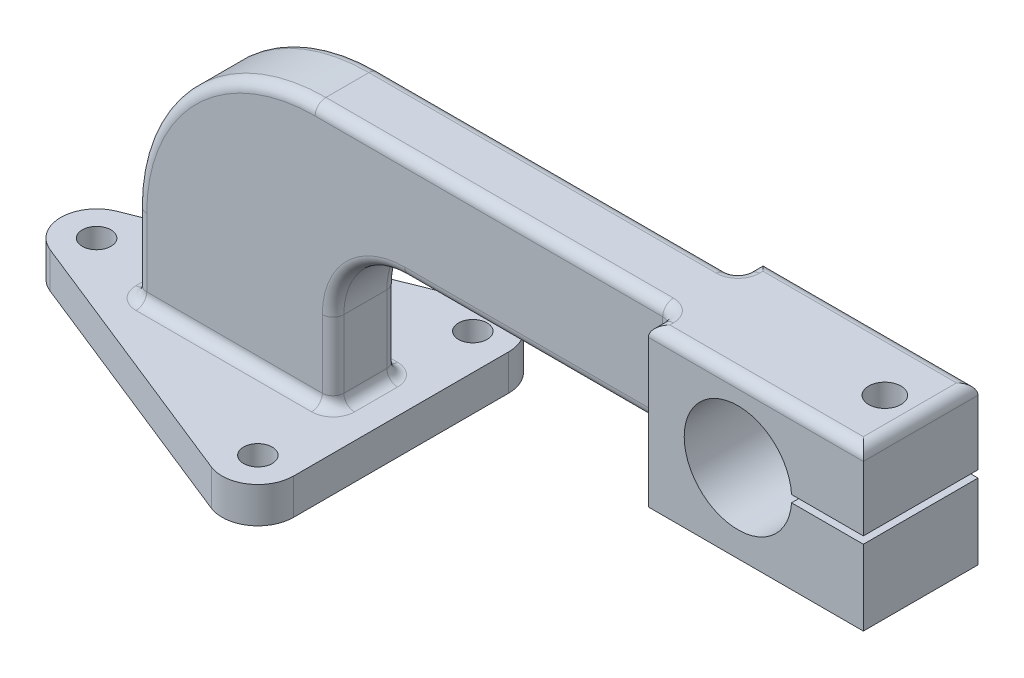
SolidWorks part; units mm, degrees
material "Zoltek Panex 33"
ref_plane "Front Plane" through (0, 0, 0) normal (0, 0, 1) x (1, 0, 0)
ref_plane "Top Plane" through (0, 0, 0) normal (0, 1, 0) x (1, 0, 0)
ref_plane "Right Plane" through (0, 0, 0) normal (1, 0, 0) x (0, 0, -1)
sketch "Sketch1" plane through (0, 0, 0) normal (0, 0, 1) x (1, 0, 0)
  line L0 (-112.5, 7.6863) -> (-57.5, 7.6863)
  line L1 (-57.5, 7.6863) -> (-57.5, 29.6863)
  line L2 (-37.5, 49.6863) -> (37.5, 49.6863)
  line L3 (37.5, 49.6863) -> (37.5, 79.6863)
  line L4 (37.5, 79.6863) -> (-62.5, 79.6863)
  line L5 (-112.5, 29.6863) -> (-112.5, 7.6863)
  arc A0 (-57.5, 29.6863) -> (-37.5, 49.6863) centre (-37.5, 29.6863) cw
  arc A1 (-62.5, 79.6863) -> (-112.5, 29.6863) centre (-62.5, 29.6863) ccw
  point P10 (0, 49.6863)
  point P11 (-132.8554, 79.6863)
  point P13 (0, 0)
  point P14 (0, 0)
  point P15 (0, 0)
  point P16 (-112.5, 29.6863)
  dimension "D3" = 20
  dimension "D4" = 50
  dimension "D1" = 55
  dimension "D2" = 30
  dimension "D5" = 95
  dimension "D6" = 22
  dimension "D7" = 22
extrude "Boss-Extrude1" add sketch "Sketch1" along normal mid plane 18
sketch "Sketch3" plane through (0, 7.6863, 0) normal (0, -1, 0) x (1, 0, 0)
  line L0 (-112.5, 0) -> (-57.5, 0) construction
  line L1 (-112.5, 9) -> (-112.5, -9) construction
  line L2 (-57.5, 9) -> (-57.5, -9) construction
  line L3 (-47.5, 30) -> (-47.5, -30)
  line L4 (-61.2139, -39.2848) -> (-136.2139, -9.2848)
  line L5 (-136.2139, 9.2848) -> (-61.2139, 39.2848)
  line L6 (-159.4258, 0) -> (-47.5, 0) construction
  arc A0 (-47.5, 30) -> (-61.2139, 39.2848) centre (-57.5, 30) ccw
  arc A1 (-47.5, -30) -> (-61.2139, -39.2848) centre (-57.5, -30) cw
  arc A2 (-136.2139, -9.2848) -> (-136.2139, 9.2848) centre (-132.5, 0) cw
  circle A3 centre (-132.5, 0) radius 4
  circle A4 centre (-57.5, -30) radius 4
  circle A5 centre (-57.5, 30) radius 4
  point P21 (0, 0)
  point P22 (0, 0)
  line M9 (-112.5, -9) -> (-57.5, -9)
  line M10 (-57.5, -9) -> (-57.5, 9)
  line M11 (-57.5, 9) -> (-112.5, 9)
  line M12 (-112.5, 9) -> (-112.5, -9)
  dimension "D1" = 10
  dimension "D5" = 8
  dimension "D2" = 30
  dimension "D3" = 75
  dimension "D4" = 20
extrude "Boss-Extrude2" add sketch "Sketch3" along normal blind 10 contours A2 L4 A1 L3 A0 L5 A5 A4 A3 M9 M12 M11 M10 | M12 M9 M10 M11
sketch "Sketch4" plane through (37.5, 0, 0) normal (1, 0, 0) x (0, 0, -1)
  line L0 (0, 79.6863) -> (0, 49.6863) construction
  line L1 (-9, 79.6863) -> (9, 79.6863) construction
  line L2 (-9, 49.6863) -> (9, 49.6863) construction
  line L3 (-16, 79.6863) -> (16, 79.6863)
  line L4 (16, 79.6863) -> (16, 35.6863)
  line L5 (16, 35.6863) -> (-16, 35.6863)
  line L6 (-16, 35.6863) -> (-16, 79.6863)
  line L7 (0, 79.6863) -> (0, 35.6863) construction
  point P8 (0, 0)
  point P12 (0, 0)
  dimension "D1" = 32
  dimension "D2" = 44
extrude "Boss-Extrude3" add sketch "Sketch4" along normal blind 60 contours L4 L5 L6 L3
sketch "Sketch5" plane through (0, 0, 16) normal (0, 0, 1) x (1, 0, 0)
  line L0 (37.5, 57.6863) -> (97.5, 57.6863) construction
  line L1 (37.5, 35.6863) -> (37.5, 79.6863) construction
  line L2 (97.5, 35.6863) -> (97.5, 79.6863) construction
  circle A0 centre (62.5, 57.6863) radius 15
  dimension "D1" = 30
  dimension "D2" = 35
extrude "Cut-Extrude1" cut sketch "Sketch5" against normal blind 60
sketch "Sketch6" plane through (0, 0, 16) normal (0, 0, 1) x (1, 0, 0)
  line L0 (97.5, 35.6863) -> (97.5, 79.6863) construction
  line L1 (67.3117, 58.6863) -> (121.3906, 58.6863)
  line L2 (67.3117, 58.6863) -> (67.3117, 56.6863)
  line L3 (67.3117, 56.6863) -> (121.3906, 56.6863)
  line L4 (121.3906, 58.6863) -> (121.3906, 56.6863)
  line L5 (77.5, 57.6863) -> (97.5, 57.6863) construction
  line L6 (67.3117, 57.6863) -> (121.3906, 57.6863) construction
  circle A0 centre (62.5, 57.6863) radius 15 construction
  dimension "D1" = 2
extrude "Cut-Extrude2" cut sketch "Sketch6" against normal blind 60
sketch "Sketch7" plane through (0, 79.6863, 0) normal (0, 1, 0) x (1, 0, 0)
  line L0 (97.5, 0) -> (14.8637, 0) construction
  line L1 (97.5, -16) -> (97.5, 16) construction
  circle A0 centre (87.5, 0) radius 4.5
  point P9 (95.9926, -2.9025)
  point P10 (97.5, -16)
  dimension "D1" = 9
  dimension "D2" = 10
  dimension "D3" = 16
extrude "Cut-Extrude3" cut sketch "Sketch7" against normal through all
fillet "Fillet1" radius 3 24 edges at (37.5, 64.6863, 9) (37.5, 64.6863, -9) (-112.5, 18.6863, -9) (-97.8553, 65.0417, -9) (-112.5, 18.6863, 9) (-97.8553, 65.0417, 9) (37.5, 49.6863, 0) (0, 49.6863, -9) (-51.6421, 43.8285, -9) (-57.5, 18.6863, -9) (-57.5, 18.6863, 9) (-51.6421, 43.8285, 9) (0, 49.6863, 9) (37.5, 79.6863, -12.5) (67.5, 79.6863, -16) (97.5, 79.6863, 0) (67.5, 79.6863, 16) (37.5, 79.6863, 12.5) (-12.5, 79.6863, -9) (-12.5, 79.6863, 9) (-57.5, 7.6863, 0) (-85, 7.6863, -9) (-112.5, 7.6863, 0) (-85, 7.6863, 9)
